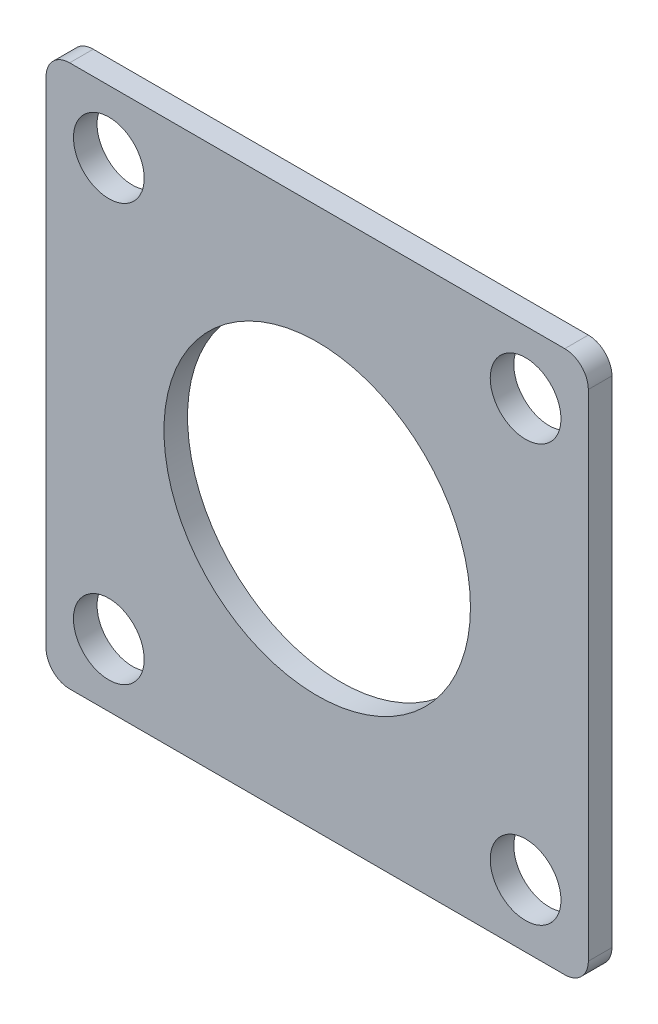
SolidWorks part; units mm, degrees
ref_plane "前视基准面" through (0, 0, 0) normal (0, 0, 1) x (1, 0, 0)
ref_plane "上视基准面" through (0, 0, 0) normal (0, 1, 0) x (1, 0, 0)
ref_plane "右视基准面" through (0, 0, 0) normal (1, 0, 0) x (0, 0, -1)
sketch "草图1" plane through (0, 0, 0) normal (0, 0, 1) x (1, 0, 0)
  line L0 (0, 0) -> (71.3135, 0) construction
  line L1 (0, 0) -> (0, 55.9796) construction
  line L2 (11.5, 11.5) -> (-11.5, -11.5) construction
  line L3 (-11.5, 11.5) -> (11.5, 11.5)
  line L4 (-11.5, 11.5) -> (-11.5, -11.5)
  line L5 (-11.5, -11.5) -> (11.5, -11.5)
  line L6 (11.5, 11.5) -> (11.5, -11.5)
  line L7 (-11.5, 11.5) -> (11.5, -11.5) construction
  circle A0 centre (0, 0) radius 12.5 construction
  circle A1 centre (-8.8388, 8.8388) radius 1.5
  circle A2 centre (-8.8388, -8.8388) radius 1.5
  circle A3 centre (8.8388, -8.8388) radius 1.5
  circle A4 centre (8.8388, 8.8388) radius 1.5
  circle A5 centre (0, 0) radius 6.5
  dimension "D2" = 25
  dimension "D3" = 3
  dimension "D4" = 13
  dimension "D1" = 23
extrude "凸台-拉伸1" add sketch "草图1" along normal blind 1
fillet "圆角1" radius 1 4 edges at (-11.5, -11.5, 0.5) (11.5, -11.5, 0.5) (11.5, 11.5, 0.5) (-11.5, 11.5, 0.5)
